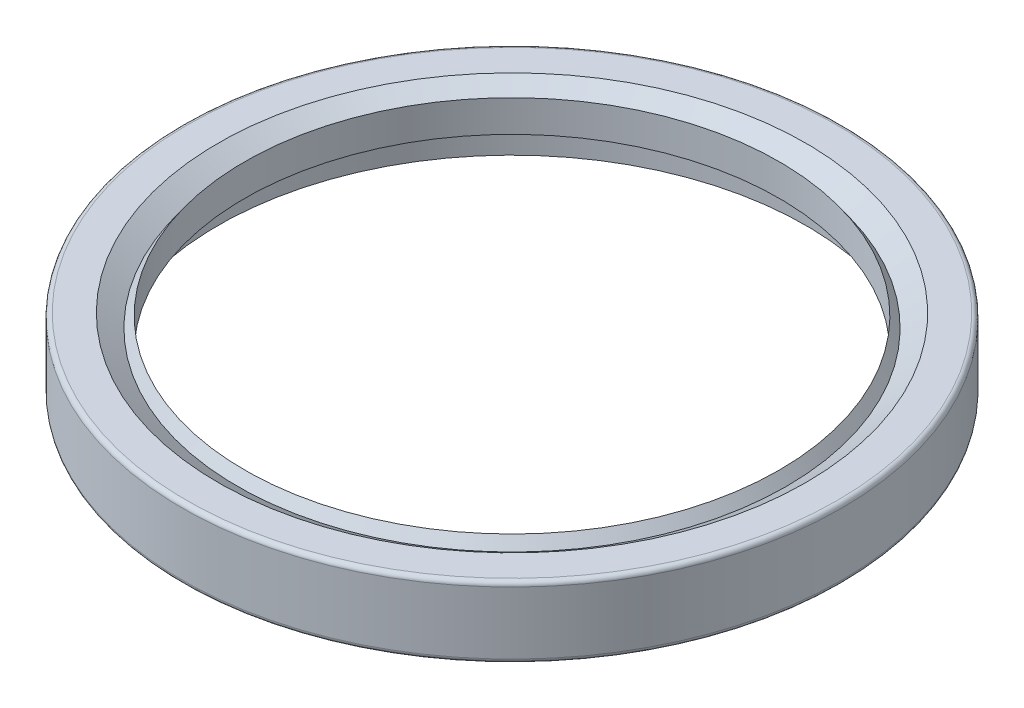
SolidWorks part; units mm, degrees
ref_plane "Piano frontale" through (0, 0, 0) normal (0, 0, 1) x (1, 0, 0)
ref_plane "Piano superiore" through (0, 0, 0) normal (0, 1, 0) x (1, 0, 0)
ref_plane "Piano destro" through (0, 0, 0) normal (1, 0, 0) x (0, 0, -1)
sketch "Schizzo1" plane through (0, 0, 0) normal (0, 0, 1) x (1, 0, 0)
  line L0 (0, 0) -> (0, 54.4068) construction
  line L1 (-1000, 0) -> (49000, 0) construction
  line L2 (-30, 48.1457) -> (-30, -10.3632) construction
  line L3 (-33, 0) -> (-36.5, 0)
  line L4 (-33, 0) -> (-33, 6.1557)
  line L5 (-33, 8) -> (-36.5, 8)
  line L6 (-37, 0.5) -> (-37, 7.5)
  line L7 (-33, 8) -> (-30.8141, 6.5344)
  line L8 (-30, 6.1331) -> (-30, 4.1442)
  line L9 (-30, 4.1442) -> (-33, 6.1557)
  line L10 (-30.8141, 6.5344) -> (-30, 7.708)
  line L11 (-30, 7.708) -> (-30, 6.1331)
  arc A0 (-36.5, 0) -> (-37, 0.5) centre (-36.5, 0.5) cw
  arc A1 (-36.5, 8) -> (-37, 7.5) centre (-36.5, 7.5) ccw
  dimension "D5" = 0.5
  dimension "D1" = 8
  dimension "D2" = 33
  dimension "D3" = 30
  dimension "D4" = 37
revolve "Rivoluzione1" add sketch "Schizzo1" angle 360 about L0
